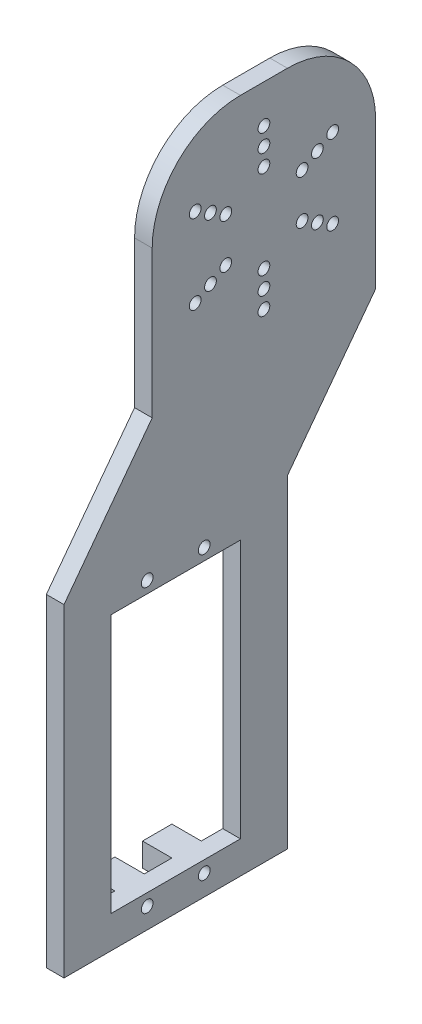
SolidWorks part; units mm, degrees
material "Polylactic Acid"
ref_plane "Front Plane" through (0, 0, 0) normal (0, 0, 1) x (1, 0, 0)
ref_plane "Top Plane" through (0, 0, 0) normal (0, 1, 0) x (1, 0, 0)
ref_plane "Right Plane" through (0, 0, 0) normal (1, 0, 0) x (0, 0, -1)
sketch "Sketch1" plane through (0, 0, 0) normal (1, 0, 0) x (0, 0, -1)
  line L0 (-19, -27.5) -> (19, -27.5)
  line L1 (19, -27.5) -> (19, 27.5)
  line L2 (19, 27.5) -> (34, 47.5)
  line L3 (34, 47.5) -> (34, 87.5)
  line L4 (34, 87.5) -> (-4, 87.5)
  line L5 (-4, 87.5) -> (-4, 47.5)
  line L6 (-4, 47.5) -> (-19, 27.5)
  line L7 (-19, 27.5) -> (-19, -27.5)
  line L8 (-4.85, -24) -> (4.85, -24) construction
  line L9 (-4.85, -24) -> (-4.85, 24) construction
  line L10 (15, 75) -> (15, 78) construction
  line L11 (-11, 22) -> (11, 22)
  line L12 (-11, 22) -> (-11, -22)
  line L13 (-11, -22) -> (11, -22)
  line L14 (11, 22) -> (11, -22)
  line L15 (21.4952, 71.25) -> (24.0933, 72.75) construction
  line L16 (21.4952, 63.75) -> (24.0933, 62.25) construction
  line L21 (15, 60) -> (15, 57) construction
  line L22 (8.5048, 63.75) -> (5.9067, 62.25) construction
  line L23 (8.5048, 71.25) -> (5.9067, 72.75) construction
  line L24 (15, 67.5) -> (15, 75) construction
  circle A0 centre (-4.85, -24) radius 1
  circle A1 centre (4.85, -24) radius 1
  circle A2 centre (4.85, 24) radius 1
  circle A3 centre (-4.85, 24) radius 1
  circle A8 centre (15, 75) radius 1
  circle A9 centre (15, 78) radius 1
  circle A10 centre (15, 81) radius 1
  circle A11 centre (21.4952, 71.25) radius 1
  circle A12 centre (24.0933, 72.75) radius 1
  circle A13 centre (26.6913, 74.25) radius 1
  circle A14 centre (21.4952, 63.75) radius 1
  circle A15 centre (24.0933, 62.25) radius 1
  circle A16 centre (26.6913, 60.75) radius 1
  circle A17 centre (15, 60) radius 1
  circle A18 centre (15, 57) radius 1
  circle A19 centre (15, 54) radius 1
  circle A20 centre (8.5048, 63.75) radius 1
  circle A21 centre (5.9067, 62.25) radius 1
  circle A22 centre (3.3087, 60.75) radius 1
  circle A23 centre (8.5048, 71.25) radius 1
  circle A24 centre (5.9067, 72.75) radius 1
  circle A25 centre (3.3087, 74.25) radius 1
  point P23 (-11, 0)
  point P24 (-4.85, 0)
  point P25 (0, -24)
  point P26 (0, -22)
  point P28 (0, -27.5)
  point P29 (-19, 0)
  point P49 (15, 87.5)
  point P86 (-4, 67.5)
  dimension "D1" = 2
  dimension "D16" = 6
  dimension "D15" = 2
  dimension "D4" = 9.7
  dimension "D5" = 48
  dimension "D6" = 22
  dimension "D7" = 44
  dimension "D8" = 38
  dimension "D9" = 55
  dimension "D10" = 15
  dimension "D11" = 20
  dimension "D14" = 3
  dimension "D17" = 7.5
  dimension "D12" = 40
  dimension "D13" = 3
  dimension "D2" = 2
  dimension "D3" = 2
extrude "Boss-Extrude1" add sketch "Sketch1" along normal mid plane 3
fillet "Fillet1" radius 15 2 edges at (0, 87.5, -34) (0, 87.5, 4)
sketch "Sketch2" plane through (-1.5, 0, 0) normal (1, 0, 0) x (0, 0, -1)
  line L0 (-11, -22) -> (11, -22) construction
  line L1 (-7.35, -26) -> (-2.35, -26)
  line L2 (-7.35, -26) -> (-7.35, -22)
  line L3 (-7.35, -22) -> (-2.35, -22)
  line L4 (-2.35, -26) -> (-2.35, -22)
  line L5 (-7.35, -26) -> (-2.35, -22) construction
  line L6 (-7.35, -22) -> (-2.35, -26) construction
  line L7 (2.35, -26) -> (7.35, -26)
  line L8 (2.35, -26) -> (2.35, -22)
  line L9 (2.35, -22) -> (7.35, -22)
  line L10 (7.35, -26) -> (7.35, -22)
  line L11 (2.35, -26) -> (7.35, -22) construction
  line L12 (2.35, -22) -> (7.35, -26) construction
  line L13 (2.35, 22) -> (7.35, 22)
  line L14 (2.35, 22) -> (2.35, 26)
  line L15 (2.35, 26) -> (7.35, 26)
  line L16 (7.35, 22) -> (7.35, 26)
  line L17 (2.35, 22) -> (7.35, 26) construction
  line L18 (2.35, 26) -> (7.35, 22) construction
  line L19 (-7.35, 22) -> (-2.35, 22)
  line L20 (-7.35, 22) -> (-7.35, 26)
  line L21 (-7.35, 26) -> (-2.35, 26)
  line L22 (-2.35, 22) -> (-2.35, 26)
  line L23 (-7.35, 22) -> (-2.35, 26) construction
  line L24 (-7.35, 26) -> (-2.35, 22) construction
  line L25 (-4.85, -24) -> (4.85, -24) construction
  line L26 (-4.85, -24) -> (-4.85, 24) construction
  line L28 (-4.85, -24) -> (4.85, -24) construction
  line L29 (-4.85, -24) -> (-4.85, 24) construction
  circle A0 centre (4.85, 24) radius 1 construction
  circle A1 centre (-4.85, -24) radius 1
  circle A2 centre (-4.85, -24) radius 1 construction
  circle A3 centre (4.85, -24) radius 1
  circle A4 centre (4.85, 24) radius 1
  circle A5 centre (-4.85, 24) radius 1
  point P0 (-4.85, -24)
  point P9 (4.85, -24)
  point P15 (4.85, 24)
  point P20 (-4.85, 24)
  point P28 (1.248, -24)
  point P29 (0, 0)
  dimension "D1" = 5
  dimension "D4" = 2
  dimension "D5" = 2
  dimension "D2" = 2
  dimension "D3" = 2
extrude "Boss-Extrude2" add sketch "Sketch2" against normal blind 5
